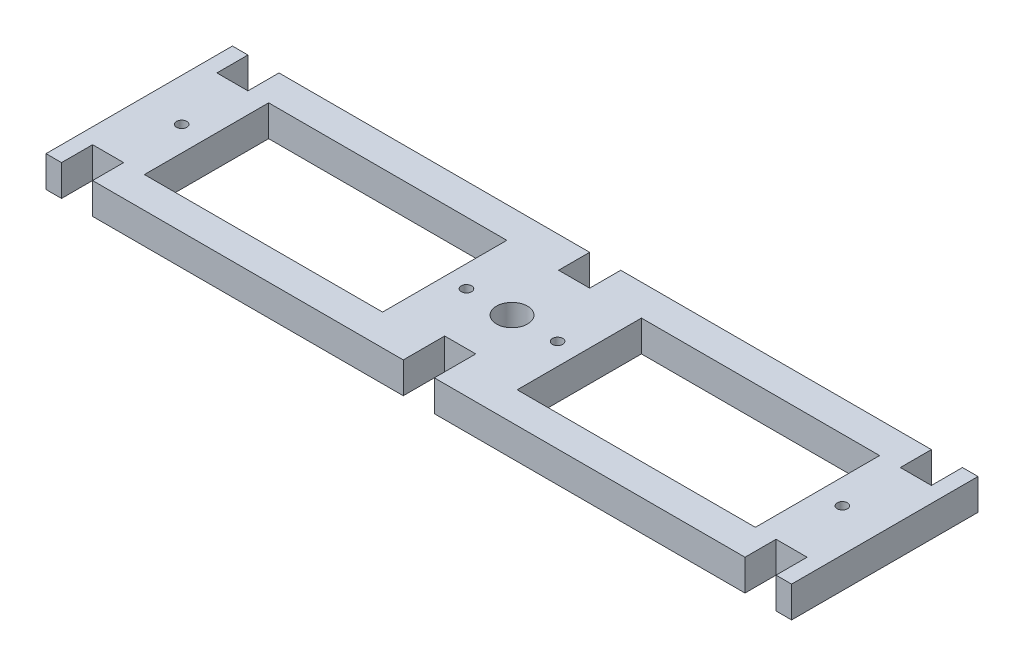
SolidWorks part; units mm, degrees
ref_plane "前视基准面" through (0, 0, 0) normal (0, 0, 1) x (1, 0, 0)
ref_plane "上视基准面" through (0, 0, 0) normal (0, 1, 0) x (1, 0, 0)
ref_plane "右视基准面" through (0, 0, 0) normal (1, 0, 0) x (0, 0, -1)
other "Configuration Table"
sketch "草图1" plane through (0, 0, 0) normal (0, 1, 0) x (1, 0, 0)
  line L0 (-44.9057, 28.8433) -> (-44.9057, 10.8433)
  line L1 (-44.9057, 10.8433) -> (-43.4057, 10.8433)
  line L2 (-43.4057, 10.8433) -> (-43.4057, 13.8433)
  line L3 (-43.4057, 13.8433) -> (-40.4057, 13.8433)
  line L4 (-40.4057, 13.8433) -> (-40.4057, 10.8433)
  line L5 (-40.4057, 10.8433) -> (-10.4057, 10.8433)
  line L6 (-10.4057, 10.8433) -> (-10.4057, 14.8433)
  line L7 (-10.4057, 14.8433) -> (-7.4057, 14.8433)
  line L8 (-44.9057, 28.8433) -> (-43.4057, 28.8433)
  line L9 (-43.4057, 28.8433) -> (-43.4057, 25.8433)
  line L10 (-43.4057, 25.8433) -> (-40.4057, 25.8433)
  line L11 (-40.4057, 25.8433) -> (-40.4057, 28.8433)
  line L12 (-40.4057, 28.8433) -> (-10.4057, 28.8433)
  line L13 (-10.4057, 28.8433) -> (-10.4057, 25.8433)
  line L14 (-10.4057, 25.8433) -> (-7.4057, 25.8433)
  line L15 (-8.9057, 25.8433) -> (-8.9057, 14.8433) construction
  line L16 (-7.4057, 28.8433) -> (-7.4057, 25.8433)
  line L17 (-7.4057, 10.8433) -> (-7.4057, 14.8433)
  line L18 (22.5943, 10.8433) -> (-7.4057, 10.8433)
  line L19 (22.5943, 13.8433) -> (22.5943, 10.8433)
  line L20 (25.5943, 10.8433) -> (25.5943, 13.8433)
  line L21 (25.5943, 13.8433) -> (22.5943, 13.8433)
  line L22 (27.0943, 10.8433) -> (25.5943, 10.8433)
  line L23 (27.0943, 28.8433) -> (27.0943, 10.8433)
  line L24 (27.0943, 28.8433) -> (25.5943, 28.8433)
  line L25 (25.5943, 28.8433) -> (25.5943, 25.8433)
  line L26 (22.5943, 25.8433) -> (22.5943, 28.8433)
  line L27 (25.5943, 25.8433) -> (22.5943, 25.8433)
  line L28 (22.5943, 28.8433) -> (-7.4057, 28.8433)
  line L29 (-44.9057, 19.8433) -> (27.0943, 19.8433) construction
  line L30 (-8.9057, 19.8433) -> (-13.3057, 19.8433) construction
  line L31 (-8.9057, 16.5892) -> (-8.9057, 9.2922) construction
  line L32 (-13.3057, 19.8433) -> (-40.8057, 19.8433) construction
  line L33 (-2.4057, 25.8433) -> (-2.4057, 13.8433)
  line L34 (-15.4057, 13.8433) -> (-38.4057, 13.8433)
  line L35 (-38.4057, 13.8433) -> (-38.4057, 25.8433)
  line L36 (-38.4057, 25.8433) -> (-15.4057, 25.8433)
  line L37 (-15.4057, 25.8433) -> (-15.4057, 13.8433)
  line L38 (-2.4057, 13.8433) -> (20.5943, 13.8433)
  line L39 (20.5943, 25.8433) -> (-2.4057, 25.8433)
  line L40 (20.5943, 13.8433) -> (20.5943, 25.8433)
  circle A0 centre (-13.3057, 19.8433) radius 0.5
  circle A1 centre (-40.8057, 19.8433) radius 0.5
  circle A2 centre (-4.5057, 19.8433) radius 0.5
  circle A3 centre (22.9943, 19.8433) radius 0.5
  circle A4 centre (-8.9057, 19.8433) radius 1.5
extrude "凸台-拉伸1" add sketch "草图1" along normal blind 3 contours L26 L28 L16 L14 L13 L12 L11 L10 L9 L8 L0 L1 L2 L3 L4 L5 L6 L7 L17 L18 L19 L21 L20 L22 L23 L24 L25 L27 A4 A2 A1 A0 L40 L38 L33 L39 L36 L37 L34 L35 A3
